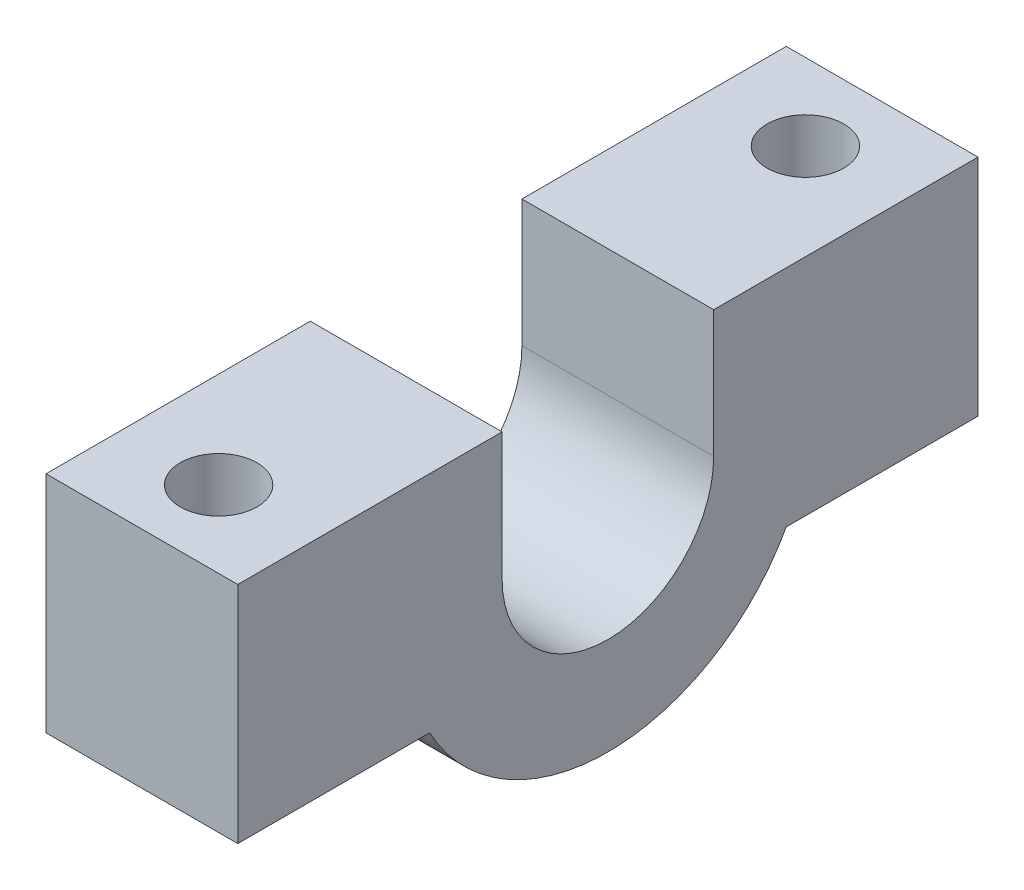
SolidWorks part; units mm, degrees
ref_plane "Front Plane" through (0, 0, 0) normal (0, 0, 1) x (1, 0, 0)
ref_plane "Top Plane" through (0, 0, 0) normal (0, 1, 0) x (1, 0, 0)
ref_plane "Right Plane" through (0, 0, 0) normal (1, 0, 0) x (0, 0, -1)
sketch "Sketch2" plane through (0, 0, 0) normal (1, 0, 0) x (0, 0, -1)
  line L0 (-10.035, 0) -> (10.035, 0) construction
  line L1 (-11.035, 0) -> (-38.6011, 0) construction
  line L2 (11.035, 0) -> (83.965, 0) construction
  line L3 (0, 0) -> (95, 0) construction
  line L4 (106.035, 0) -> (133.6011, 0) construction
  line L5 (-18.6011, -10.16) -> (-38.6011, -10.16)
  line L6 (18.6011, -10.16) -> (76.3989, -10.16) construction
  line L7 (113.6011, -10.16) -> (133.6011, -10.16) construction
  line L8 (-38.6011, 0) -> (-38.6011, -10.16)
  line L9 (133.6011, 0) -> (133.6011, -10.16) construction
  line L10 (-38.6011, 0) -> (-38.6011, 13.245)
  line L11 (-38.6011, 13.245) -> (-11.035, 13.245)
  line L12 (-11.035, 13.245) -> (-11.035, 0)
  line L13 (11.035, 0) -> (11.035, 13.245)
  line L14 (11.035, 13.245) -> (83.965, 13.245) construction
  line L15 (83.965, 13.245) -> (83.965, 0) construction
  line L16 (106.035, 0) -> (106.035, 13.245) construction
  line L17 (106.035, 13.245) -> (133.6011, 13.245) construction
  line L18 (133.6011, 13.245) -> (133.6011, 0) construction
  line L19 (11.035, 13.245) -> (38.6011, 13.245)
  line L20 (38.6011, 13.245) -> (38.6011, -10.16)
  line L21 (38.6011, -10.16) -> (18.6011, -10.16)
  arc A0 (-10.035, 0) -> (10.035, 0) centre (0, 0) ccw construction
  arc A1 (-11.035, 0) -> (11.035, 0) centre (0, 0) ccw
  arc A2 (84.965, 0) -> (105.035, 0) centre (95, 0) ccw construction
  arc A3 (83.965, 0) -> (106.035, 0) centre (95, 0) ccw construction
  arc A4 (-18.6011, -10.16) -> (18.6011, -10.16) centre (0, 0) ccw
  arc A5 (76.3989, -10.16) -> (113.6011, -10.16) centre (95, 0) ccw construction
  dimension "D6" = 10.16
  dimension "D1" = 20.07
  dimension "D3" = 95
  dimension "D5" = 20
  dimension "D7" = 10.16
  dimension "D8" = 10.16
  dimension "D9" = 13.245
  dimension "D2" = 1
  dimension "D4" = 1
extrude "Boss-Extrude1" add sketch "Sketch2" along normal blind 20
sketch "Sketch3" plane through (0, 13.245, 0) normal (0, 1, 0) x (1, 0, 0)
  line L0 (0, -38.6011) -> (0, -18.6011) construction
  line L1 (0, -38.6011) -> (0, -18.6011) construction
  line L2 (10, 0) -> (10, -30.6) construction
  line L3 (20, -38.6011) -> (0, -38.6011) construction
  line L4 (10, 0) -> (10, 30.6) construction
  line L5 (0, 0) -> (30.8763, 0) construction
  line L8 (20, -38.6011) -> (0, -38.6011) construction
  line L9 (20, -11.035) -> (20, -38.6011) construction
  circle A0 centre (10, -30.6) radius 4
  circle A2 centre (10, 30.6) radius 4
  point P2 (0, 0)
  point P14 (10, -38.6011)
  dimension "D1" = 8
  dimension "D2" = 61.2
extrude "Cut-Extrude1" cut sketch "Sketch3" against normal up to next
